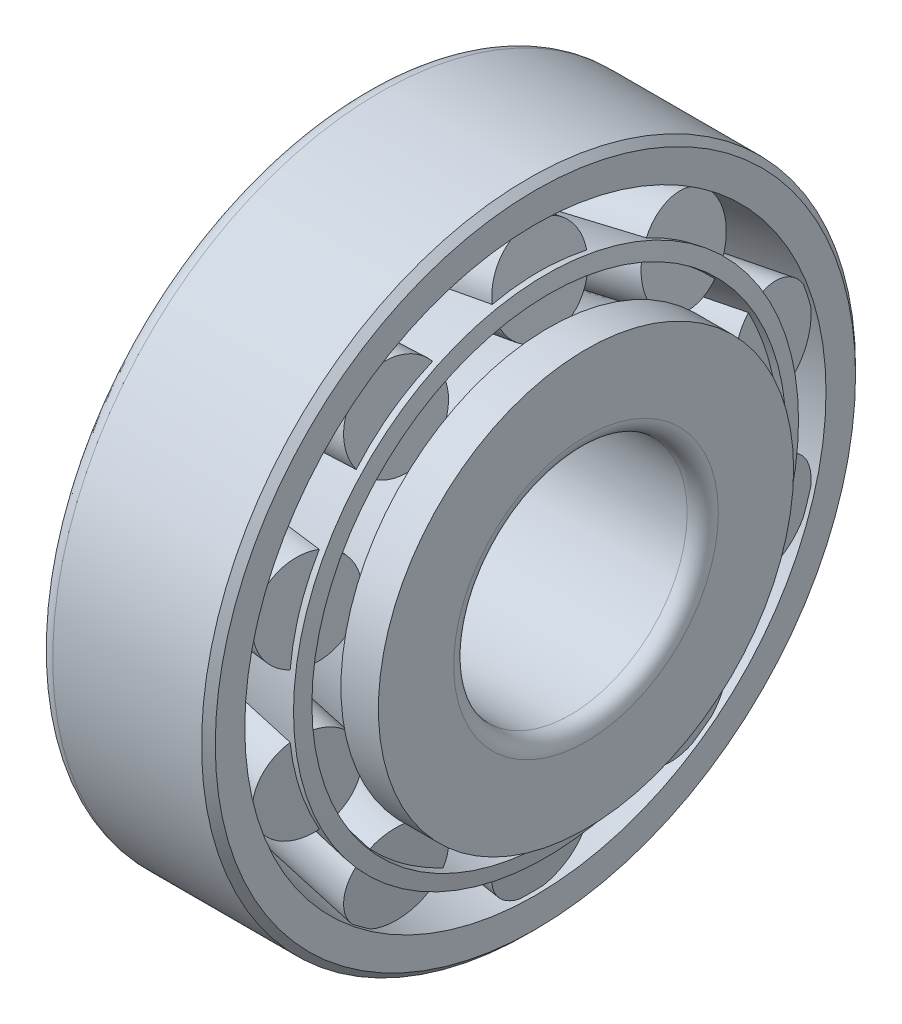
SolidWorks part; units mm, degrees
revolve "OuterRace" add sketch "OutRacSke" angle 360 about L5
sketch "OutRacSke" plane through (0, 0, 0) normal (0, 0, 1) x (1, 0, 0)
  line L0 (-3.25, 18.6648) -> (-14.25, 16.636)
  line L1 (-14.25, 16.636) -> (-14.25, 20)
  line L2 (-13.25, 21) -> (-3.69, 21)
  line L3 (-3.69, 21) -> (-3.25, 20.56)
  line L4 (-3.25, 20.56) -> (-3.25, 18.6648)
  line L5 (-42.5, 0) -> (42.5, 0) construction
  arc A0 (-14.25, 20) -> (-13.25, 21) centre (-13.25, 20) cw
  dimension "cup_radius" = 1
  dimension "OD" = 42
  dimension "cup_width" = 11
  dimension "Tangle" = 10.45
  dimension "offset" = 14.25
  dimension "chamfer" = 0.44
  dimension "D8" = 45
  dimension "cup_SID" = 33.272
ref_plane "Plane1" through (0, 0, 0) normal (0, 0, 1) x (1, 0, 0)
ref_plane "Plane2" through (0, 0, 0) normal (0, 1, 0) x (1, 0, 0)
ref_plane "Plane3" through (0, 0, 0) normal (1, 0, 0) x (0, 0, -1)
sketch "Clipboard" plane through (0, 0, 0) normal (0, 0, 1) x (1, 0, 0)
  line L0 (0, 0) -> (10, 0) construction
  line L1 (0, 0) -> (32.7665, -5.7776)
  line L2 (0, 0) -> (14.7721, 2.6047)
  line L3 (0, 0) -> (41.3619, -7.2932)
  line L4 (0, 0) -> (-9.894, -0.3455)
  line L5 (0, 0) -> (-6.075, 14.25)
  dimension "Bore" = 15
  dimension "Count" = 10
  dimension "Show_count" = 10
  dimension "Max_count" = 10
  dimension "Min_count" = 2
  dimension "Race_OD" = 42
  dimension "Race_ID" = 33.272
  dimension "cyl_len" = 9.9
  dimension "Roller_diameter" = 6.075
  dimension "OA_width" = 14.25
sketch "RolDetSke" plane through (0, 0, 0) normal (0, 0, 1) x (1, 0, 0)
  line L0 (-12.6991, 13.9174) -> (-13.25, 16.9045)
  line L1 (-12.6991, 13.9174) -> (-2.9633, 15.7131)
  line L2 (-3.5142, 18.7002) -> (-2.9633, 15.7131)
  line L4 (-41.1331, 8.6731) -> (8.5425, 17.8351) construction
  line L5 (-3.5142, 18.7002) -> (-13.25, 16.9045)
  line L9 (-3.25, 18.6648) -> (-14.25, 16.636) construction
  dimension "cyl_len" = 9.9
  dimension "Roller_diameter" = 6.075
  dimension "dy" = 16.9045
  dimension "D2" = 13.25
revolve "RollerDetailed" add sketch "RolDetSke" angle 360 about L4
sketch "RolSimSke" plane through (0, 0, 0) normal (0, 0, 1) x (1, 0, 0)
  line L0 (0, 0) -> (-32, 0) construction
  line L1 (-13.25, 16.9045) -> (-3.5142, 18.7002)
  line L2 (-13.25, 16.9045) -> (-12.1481, 10.9303)
  line L3 (-12.1481, 10.9303) -> (-2.4123, 12.7259)
  line L4 (-3.5142, 18.7002) -> (-2.4123, 12.7259)
  dimension "Tangle" = 10.45
  dimension "Roller_diameter" = 6.075
  dimension "dy" = 16.9045
  dimension "dx" = 13.25
revolve "RollersSimplified" [suppressed] add sketch "RolSimSke" angle 360 about L0
ref_axis "Axis1" through (-50, 0, 0) along (1, 0, 0)
pattern_circular "RollersDetailed" count 10 every 36 about axis through (-50, 0, 0) along (1, 0, 0) of "RollerDetailed"
sketch "InsRacSke" plane through (0, 0, 0) normal (0, 0, 1) x (1, 0, 0)
  line L0 (-12.1986, 11.2341) -> (-13, 11.2341)
  line L1 (-14.25, 20) -> (-14.25, -20) construction
  line L2 (-13, 11.2341) -> (-13, 7.94)
  line L3 (-13, 7.94) -> (-12.56, 7.5)
  line L4 (-12.56, 7.5) -> (-1, 7.5)
  line L5 (0, 8.5) -> (0, 13.3334)
  line L6 (0, 13.3334) -> (-2.4068, 13.3334)
  line L7 (-2.4068, 13.3334) -> (-2.4068, 12.7259)
  line L8 (-2.4068, 12.7259) -> (-12.1426, 10.9303)
  line L9 (-12.1426, 10.9303) -> (-12.1986, 11.2341)
  line L10 (-42.5, 0) -> (42.5, 0) construction
  arc A0 (-1, 7.5) -> (0, 8.5) centre (-1, 8.5) ccw
  dimension "Tangle" = 10.45
  dimension "chamfer" = 0.44
  dimension "Bore" = 15
  dimension "cyl_len" = 9.9
  dimension "dy" = 10.9303
  dimension "dx" = 12.1426
  dimension "D11" = 45
  dimension "D2" = 14.25
revolve "InnerRace" add sketch "InsRacSke" angle 360 about L10
sketch "CagSpiSke" plane through (0, 0, 0) normal (0, 0, 1) x (1, 0, 0)
  line L3 (-2.4765, 15.7187) -> (-12.6991, 13.8333)
  line L4 (-13.0239, 13.3616) -> (-12.877, 12.565)
  line L6 (-42.5, 0) -> (42.5, 0) construction
  arc A1 (-12.6991, 13.8333) -> (-13.0239, 13.3616) centre (-12.6256, 13.435) ccw
  dimension "Tangle" = 10.45
  dimension "radius" = 0.405
  dimension "dx" = 12.6991
  dimension "dy" = 13.8333
  dimension "offset" = 1.215
revolve "CageSpine" add sketch "CagSpiSke" angle 360 about L6
equation "\"OD@OutRacSke\" = \"Race_OD@Clipboard\""
equation "\"cup_SID@OutRacSke\" = \"Race_ID@Clipboard\""
equation "\"chamfer@OutRacSke\" = \"cup_width@OutRacSke\" / 25"
equation "\"offset@OutRacSke\" = \"OA_width@Clipboard\""
equation "\"D2@RolDetSke\" = \"offset@OutRacSke\" - \"cup_radius@OutRacSke\""
equation "\"dy@RolDetSke\" =  ( ( \"Race_ID@Clipboard\" / 2 ) + ( \"cup_radius@OutRacSke\" ) * tan(\"Tangle@OutRacSke\" * 3.141592654/180) ) * 1.005"
equation "\"cyl_len@RolDetSke\" = \"cyl_len@Clipboard\""
equation "\"Roller_diameter@RolDetSke\" = \"Roller_diameter@Clipboard\""
equation "\"dx@RolSimSke\" = \"offset@OutRacSke\" - \"cup_radius@OutRacSke\""
equation "\"dy@RolSimSke\" =  ( ( \"Race_ID@Clipboard\" / 2 ) + ( \"cup_radius@OutRacSke\" ) * tan(\"Tangle@OutRacSke\" * 3.141592654/180) ) * 1.005"
equation "\"Cyl_Len@RolSimSke\" = \"cyl_len@Clipboard\""
equation "\"Roller_diameter@RolSimSke\" = \"Roller_diameter@Clipboard\""
equation "\"Bore@InsRacSke\" = \"Bore@Clipboard\""
equation "\"Tangle@InsRacSke\" = \"Tangle@OutRacSke\""
equation "\"cyl_len@InsRacSke\" = \"cyl_len@Clipboard\""
equation "\"chamfer@InsRacSke\" = \"chamfer@OutRacSke\""
equation "\"D2@InsRacSke\" = \"OA_width@Clipboard\""
equation "\"dx@InsRacSke\" = \"offset@OutRacSke\" - \"cup_radius@OutRacSke\" -  (  \"Roller_diameter@Clipboard\" * 1.005 )  * sin(\"Tangle@InsRacSke\" * 3.141592654/180)"
equation "\"dy@InsRacSke\" = ( ( \"Race_ID@Clipboard\" / 2 ) + ( \"cup_radius@OutRacSke\" ) * tan(\"Tangle@OutRacSke\" * 3.141592654/180) ) * 1.005 -  ( \"Roller_diameter@Clipboard\" )  * cos(\"Tangle@InsRacSke\" * 3.141592654/180) "
equation "\"front_groove@InsRacSke\" = \"Groove_dp@InsRacSke\" / 2"
equation "\"Tangle@CagSpiSke\" = \"Tangle@OutRacSke\""
equation "\"dx@CagSpiSke\" = ( \"offset@OutRacSke\" - \"cup_radius@OutRacSke\" ) -  (  \"Roller_diameter@Clipboard\" / 2  )  * sin(\"Tangle@InsRacSke\" * 3.141592654/180)"
equation "\"dy@CagSpiSke\" = ( ( \"Race_ID@Clipboard\" / 2 ) + ( \"cup_radius@OutRacSke\" ) * tan(\"Tangle@OutRacSke\" * 3.141592654/180) )  -  ( \"Roller_diameter@Clipboard\" / 2 )  * cos(\"Tangle@InsRacSke\" * 3.141592654/180) "
equation "\"length@CagSpiSke\" = \"cyl_len@Clipboard\" * 1.05"
equation "\"offset@CagSpiSke\" = \"Roller_diameter@Clipboard\" / 5"
equation "\"radius@CagSpiSke\" = \"offset@CagSpiSke\" / 3"
equation "\"D3@CageSpine\" = \"Roller_diameter@Clipboard\" / 6"
equation "\"Max_count@Clipboard\" = int( 3.14159265 / atn(( \"Roller_diameter@Clipboard\" / 2) / sqr( \"dy@CagSpiSke\"  *  \"dy@CagSpiSke\" - ( \"Roller_diameter@Clipboard\" / 2) *  ( \"Roller_diameter@Clipboard\" / 2))))"
equation "\"Max_count@Clipboard\" = ((sgn( \"Max_count@Clipboard\" - \"Count@Clipboard\" )-1)*( \"Max_count@Clipboard\" - \"Count@Clipboard\" ))/-2+ \"Count@Clipboard\""
equation "\"Count@RollersDetailed\" = int( \"Show_count@Clipboard\" ) "
equation "\"Count@RollersDetailed\" = ((sgn( \"Count@RollersDetailed\" - \"Max_count@Clipboard\" )-1)*( \"Count@RollersDetailed\" - \"Max_count@Clipboard\" ))/-2+ \"Max_count@Clipboard\""
equation "\"Count@RollersDetailed\" = ((sgn( \"Count@RollersDetailed\" - \"Min_count@Clipboard\" )+1)*( \"Count@RollersDetailed\" - \"Min_count@Clipboard\"))/2 +\"Min_count@Clipboard\""
equation "\"Angle@RollersDetailed\" = 360.0 / \"Max_count@Clipboard\""
equation "\"Angle@CageSpine\" =  \"Angle@RollersDetailed\" * ( \"Count@RollersDetailed\" -1 + int( \"Count@RollersDetailed\" / \"Max_count@Clipboard\" ) )  + 0.001 -  int( \"Count@RollersDetailed\" / \"Max_count@Clipboard\" ) * 0.001"
equation "\"Angle@CageSpine\" =  \"Angle@CageSpine\" * int( \"Min_count@Clipboard\" / 2) + int(1 / \"Min_count@Clipboard\")  * 0.001"
equation "\"Tangle@RolSimSke\" = \"Tangle@OutRacSke\""
